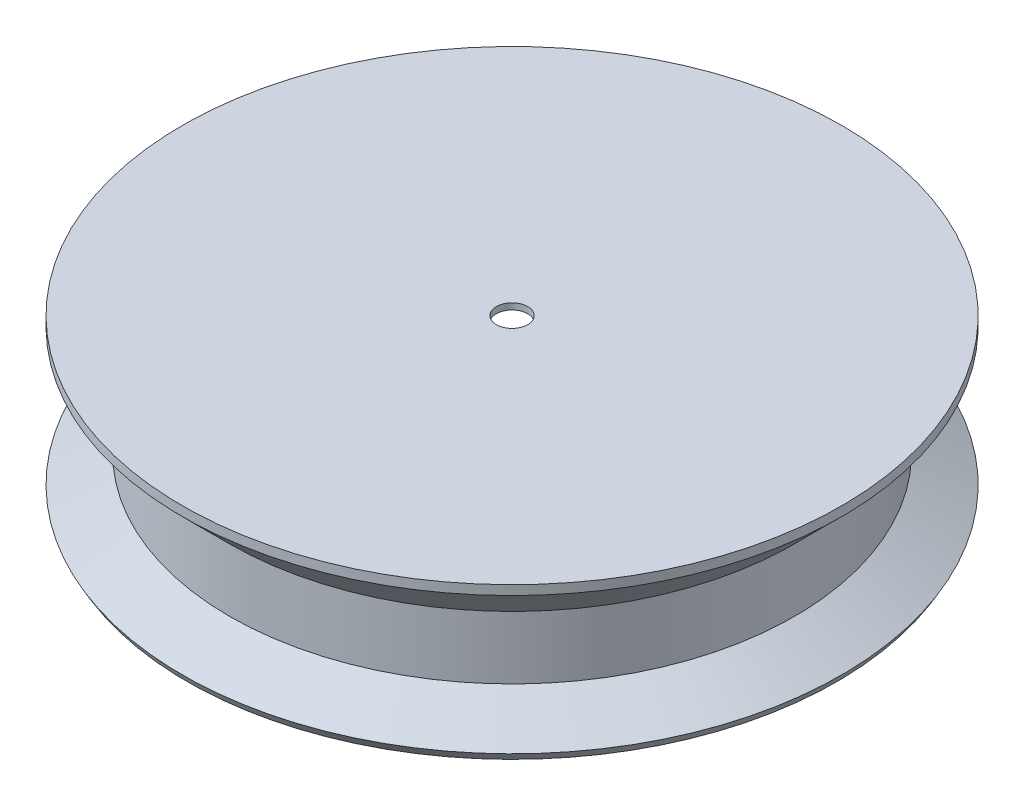
SolidWorks part; units mm, degrees
ref_plane "Plan de face" through (0, 0, 0) normal (0, 0, 1) x (1, 0, 0)
ref_plane "Plan de dessus" through (0, 0, 0) normal (0, 1, 0) x (1, 0, 0)
ref_plane "Plan de droite" through (0, 0, 0) normal (1, 0, 0) x (0, 0, -1)
sketch "Esquisse1" plane through (0, 0, 0) normal (0, 0, 1) x (1, 0, 0)
  line L0 (-5, 0) -> (-105, 0)
  line L1 (-105, 0) -> (-105, -3)
  line L2 (-105, -3) -> (-90, -18)
  line L3 (-90, -18) -> (-90, -38)
  line L4 (-90, -38) -> (-105, -46.6603)
  line L5 (-105, -46.6603) -> (-103.4908, -49.2743)
  line L6 (-103.4908, -49.2743) -> (-80, -49.2743)
  line L7 (-80, -49.2743) -> (-80, -47.2743)
  line L8 (-80, -47.2743) -> (-102.0635, -47.2743)
  line L9 (-102.0635, -47.2743) -> (-88, -39.1547)
  line L10 (-88, -39.1547) -> (-88, -17.1716)
  line L11 (-88, -17.1716) -> (-103, -2)
  line L12 (-103, -2) -> (-5, -2)
  line L13 (-5, -2) -> (-5, 0)
  dimension "D1" = 2
  dimension "D2" = 5
  dimension "D3" = 100
  dimension "D4" = 3
  dimension "D5" = 135
  dimension "D6" = 2
  dimension "D7" = 2
  dimension "D8" = 2
  dimension "D9" = 2
  dimension "D10" = 20
  dimension "D11" = 15
  dimension "D12" = 120
  dimension "D13" = 2
  dimension "D14" = 3
  dimension "D15" = 25
ref_axis "Axe1" through (0, -51.738, 0) along (0, 1, 0)
revolve "Révolution1" add sketch "Esquisse1" angle 360 about axis through (0, -51.738, 0) along (0, 1, 0)
